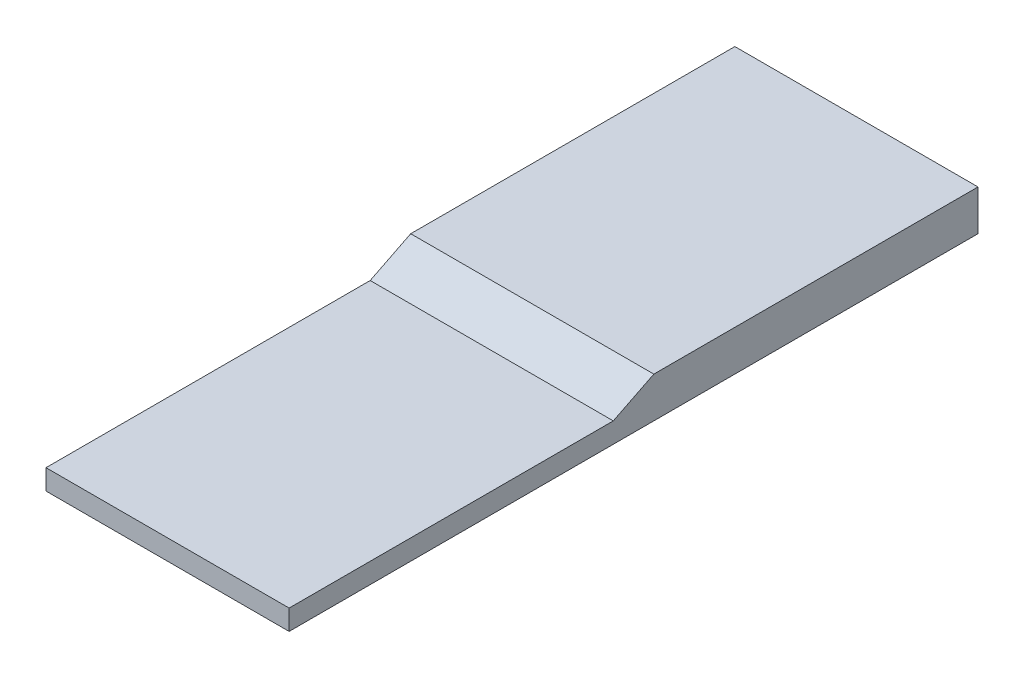
SolidWorks part; units mm, degrees
ref_plane "Front Plane" through (0, 0, 0) normal (0, 0, 1) x (1, 0, 0)
ref_plane "Top Plane" through (0, 0, 0) normal (0, 1, 0) x (1, 0, 0)
ref_plane "Right Plane" through (0, 0, 0) normal (1, 0, 0) x (0, 0, -1)
sketch "Sketch1" plane through (0, 0, 0) normal (1, 0, 0) x (0, 0, -1)
  line L0 (-406.4, 0) -> (0, 0)
  line L1 (0, 0) -> (50.8, 25.4)
  line L2 (50.8, 25.4) -> (457.2, 25.4)
  line L3 (457.2, 25.4) -> (457.2, -25.4)
  line L4 (457.2, -25.4) -> (-406.4, -25.4)
  line L5 (-406.4, -25.4) -> (-406.4, 0)
  line L6 (0, 0) -> (50.8, 0) construction
  line L7 (50.8, 0) -> (50.8, 25.4) construction
  dimension "D1" = 25.4
  dimension "D2" = 50.8
  dimension "D3" = 25.4
  dimension "D4" = 406.4
  dimension "D5" = 406.4
extrude "Boss-Extrude1" add sketch "Sketch1" along normal blind 304.8
